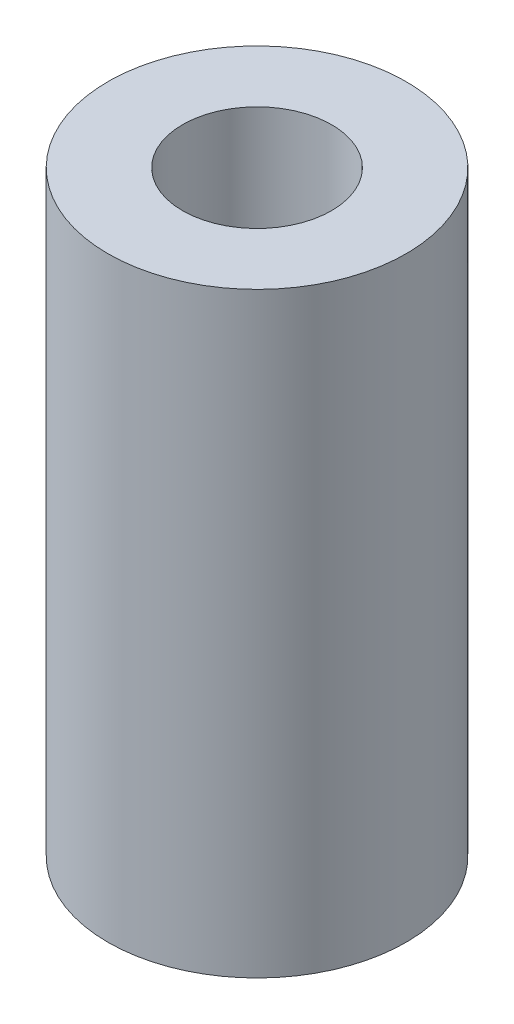
SolidWorks part; units mm, degrees
material "6061 Alloy"
ref_plane "Front Plane" through (0, 0, 0) normal (0, 0, 1) x (1, 0, 0)
ref_plane "Top Plane" through (0, 0, 0) normal (0, 1, 0) x (1, 0, 0)
ref_plane "Right Plane" through (0, 0, 0) normal (1, 0, 0) x (0, 0, -1)
sketch "Sketch1" plane through (0, 0, 0) normal (0, 1, 0) x (1, 0, 0)
  circle A0 centre (0, 0) radius 2.54
  circle A1 centre (0, 0) radius 1.27
  dimension "D1" = 2.54
  dimension "D2" = 5.08
extrude "Boss-Extrude1" add sketch "Sketch1" along normal mid plane 10.16
